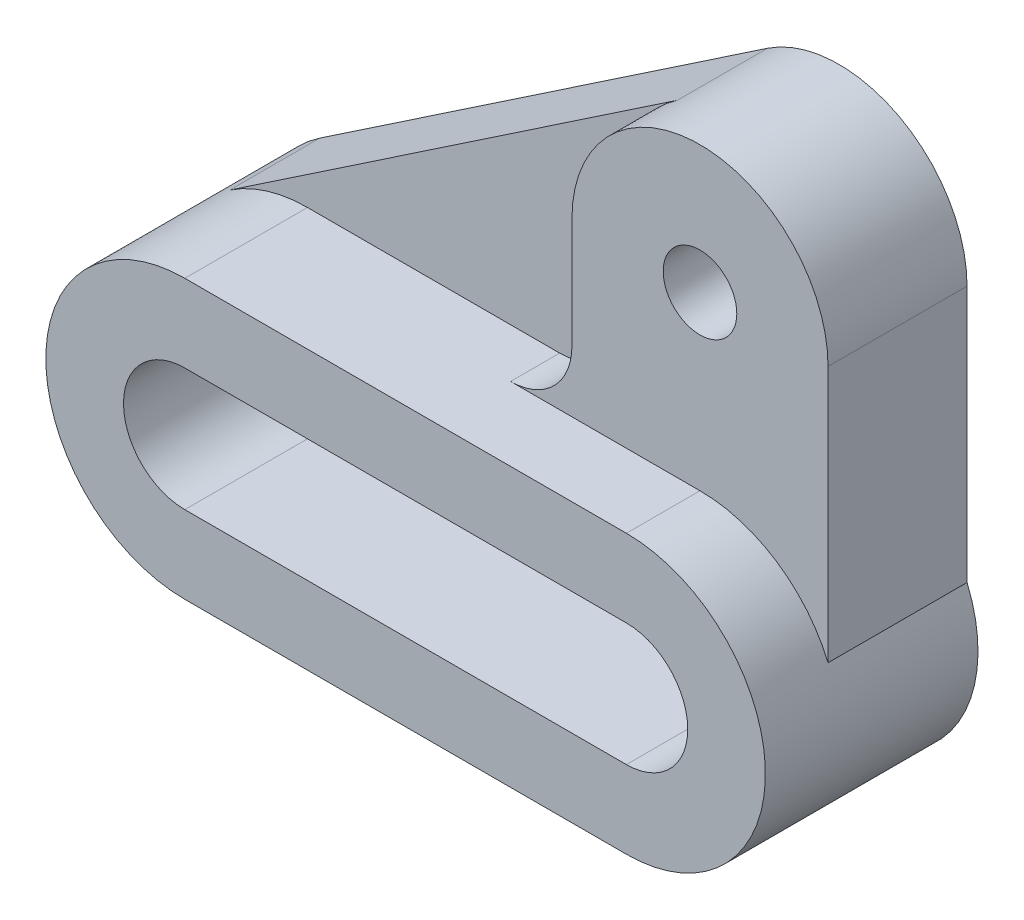
SolidWorks part; units mm, degrees
ref_plane "Front Plane" through (0, 0, 0) normal (0, 0, 1) x (1, 0, 0)
ref_plane "Top Plane" through (0, 0, 0) normal (0, 1, 0) x (1, 0, 0)
ref_plane "Right Plane" through (0, 0, 0) normal (1, 0, 0) x (0, 0, -1)
sketch "Sketch1" plane through (0, 0, 0) normal (0, 0, 1) x (1, 0, 0)
  line L0 (0, 0) -> (-108, 0) construction
  line L1 (0, -15) -> (-108, -15)
  line L2 (0, 15) -> (-108, 15)
  line L3 (0, 0) -> (-108, 0) construction
  line L4 (0, -34) -> (-108, -34)
  line L5 (0, 34) -> (-108, 34)
  arc A0 (0, -15) -> (0, 15) centre (0, 0) ccw
  arc A1 (-108, 15) -> (-108, -15) centre (-108, 0) ccw
  arc A2 (0, -34) -> (0, 34) centre (0, 0) ccw
  arc A3 (-108, 34) -> (-108, -34) centre (-108, 0) ccw
  point P3 (-54, 0)
  point P8 (-54, 0)
  dimension "D1" = 15
  dimension "D2" = 34
  dimension "D3" = 108
extrude "Boss-Extrude1" add sketch "Sketch1" along normal blind 52
sketch "Sketch2" plane through (0, 0, 0) normal (0, 0, 1) x (1, 0, 0)
  line L0 (-126.9985, 28.1968) -> (0, 28.1968)
  line L3 (31.3199, 76) -> (31.3199, 13.2311)
  line L4 (0, 28.1968) -> (31.3199, 13.2311)
  line L5 (-17.5009, 101.9741) -> (-126.9985, 28.1968)
  arc A3 (31.3199, 76) -> (-17.5009, 101.9741) centre (0, 76) ccw
  dimension "D2" = 76
extrude "Boss-Extrude2" add sketch "Sketch2" along normal blind 22 contours A3 L5 L0 L4 L3
sketch "Sketch3" plane through (0, 0, 22) normal (0, 0, 1) x (1, 0, 0)
  line L0 (-31.3199, 76) -> (-31.3199, 27.2533)
  line L1 (-31.3199, 27.2533) -> (31.3199, 13.2311)
  line L2 (31.3199, 76) -> (31.3199, 13.2311) construction
  line L3 (31.3199, 13.2311) -> (31.3199, 76)
  arc A0 (31.3199, 76) -> (-31.3199, 76) centre (0, 76) ccw
  arc A1 (0, -34) -> (0, 34) centre (0, 0) ccw construction
extrude "Boss-Extrude3" add sketch "Sketch3" along normal blind 12
hole_wizard "Ø1.0mm Clearance Dowel Hole1" positions "Sketch4" profile "Sketch5" hole size "Ø1.0" standard "ANSI Metric" end condition through all
sketch "Sketch4" plane through (0, 0, 34) normal (0, 0, 1) x (1, 0, 0)
  point P0 (0, 76)
  point P1 (0, 0)
sketch "Sketch5" plane through (0, 76, 34) normal (1, 0, 0) x (0, -1, 0)
  line L0 (0, 0) -> (0, 34)
  line L1 (0, 34) -> (9, 34)
  line L2 (9, 34) -> (9, 0)
  line L5 (9, 0) -> (0, 0)
  line L11 (0, -6.35) -> (0, 107.95) construction
  dimension "Thru Hole Dia." = 18
  dimension "Thru Hole Depth" = 34
fillet "Fillet1" radius 15 1 edges at (-31.3199, 34, 28)
